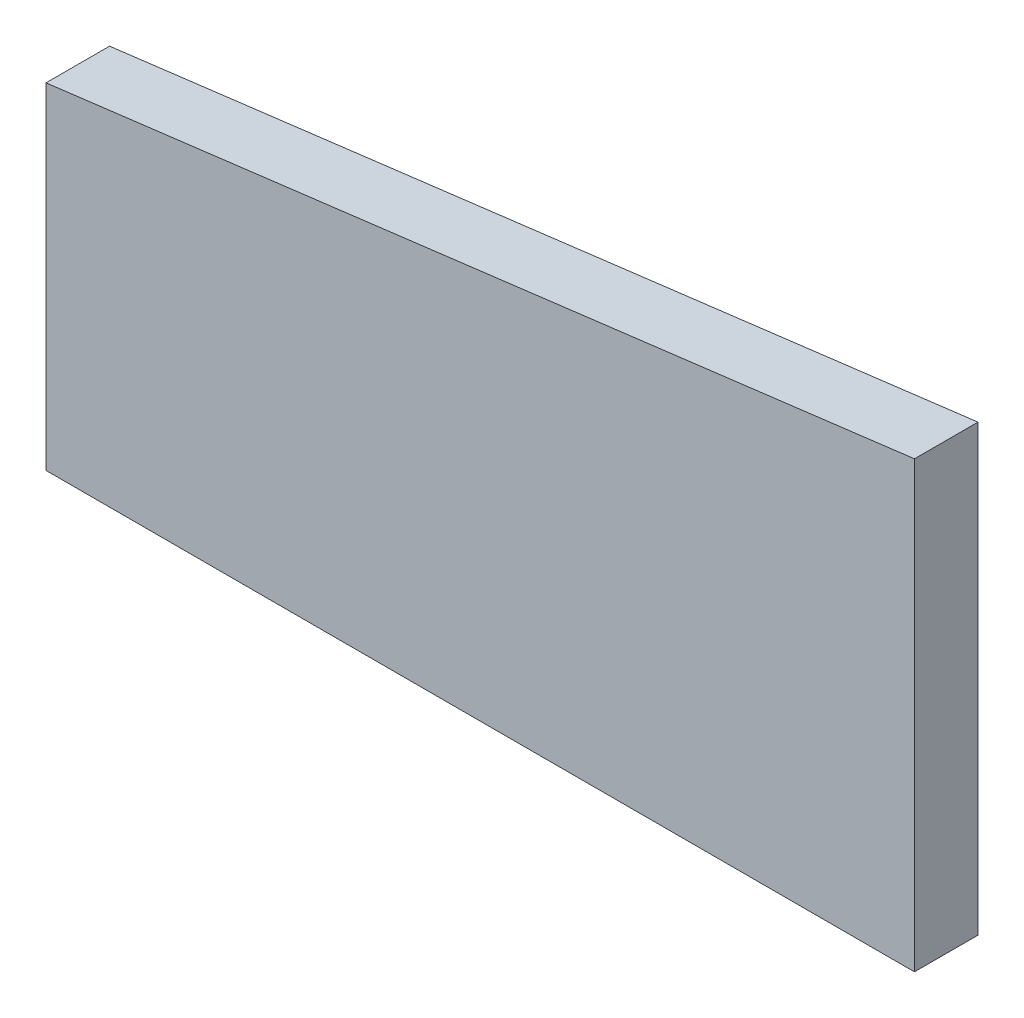
SolidWorks part; units mm, degrees
material "Pine"
ref_plane "Front Plane" through (0, 0, 0) normal (0, 0, 1) x (1, 0, 0)
ref_plane "Top Plane" through (0, 0, 0) normal (0, 1, 0) x (1, 0, 0)
ref_plane "Right Plane" through (0, 0, 0) normal (1, 0, 0) x (0, 0, -1)
sketch "Sketch2" plane through (0, 0, 0) normal (0, 0, 1) x (1, 0, 0)
  line L0 (232.7863, 27.1947) -> (486.7863, 27.1947)
  line L1 (486.7863, 27.1947) -> (486.7863, 179.5947)
  line L2 (486.7863, 179.5947) -> (79.2003, 128.6129)
  line L3 (232.7863, 128.6253) -> (232.7863, 27.1947)
  line L4 (486.7863, 160.3962) -> (81.5647, 109.7102)
  line L5 (251.8363, 131.0081) -> (251.8363, 27.1947)
  line L6 (467.7363, 158.0134) -> (251.8363, 131.0081) construction
  line L7 (467.7363, 27.1947) -> (467.7363, 158.0134)
  line L8 (251.8363, 46.2447) -> (467.7363, 46.2447) construction
  line L9 (251.8363, 131.0081) -> (251.8363, 46.2447) construction
  line L10 (467.7363, 46.2447) -> (467.7363, 158.0134) construction
  line L11 (486.7863, 160.3962) -> (484.4219, 179.2989)
  line L12 (486.7863, 27.1947) -> (486.7863, 179.5947) construction
  line L13 (486.7863, 179.5947) -> (232.7863, 147.8238) construction
  line L14 (81.5647, 109.7102) -> (60.2851, 279.8345) construction
  line L15 (232.7863, 147.8238) -> (232.7863, 27.1947) construction
  line L16 (81.5647, 109.7102) -> (79.2003, 128.6129)
  line L17 (484.4219, 179.2989) -> (230.4219, 147.528) construction
  line L22 (616.7284, 349.4357) -> (60.2851, 279.8345) construction
  line L23 (638.0079, 179.3114) -> (616.7284, 349.4357) construction
  line L24 (232.7863, 128.6253) -> (230.4219, 147.528) construction
  line L25 (232.7863, 27.1947) -> (486.7863, 27.1947) construction
  dimension "D1" = 97.13
sketch "Sketch5" plane through (0, 0, 0) normal (0, 0, 1) x (1, 0, 0)
  line L0 (226.4363, 27.1947) -> (486.7863, 27.1947)
  line L1 (486.7863, 27.1947) -> (486.7863, 179.5947)
  line L2 (486.7863, 179.5947) -> (79.2003, 128.6129)
  line L3 (226.4363, 131.0081) -> (226.4363, 27.1947)
  line L4 (486.7863, 160.3962) -> (81.5647, 109.7102)
  line L6 (467.7363, 158.0134) -> (251.8363, 131.0081) construction
  line L8 (251.8363, 46.2447) -> (467.7363, 46.2447) construction
  line L9 (251.8363, 131.0081) -> (251.8363, 46.2447) construction
  line L10 (467.7363, 46.2447) -> (467.7363, 158.0134) construction
  line L11 (486.7863, 160.3962) -> (484.4219, 179.2989)
  line L12 (486.7863, 27.1947) -> (486.7863, 179.5947) construction
  line L13 (486.7863, 179.5947) -> (232.7863, 147.8238) construction
  line L14 (81.5647, 109.7102) -> (60.2851, 279.8345) construction
  line L15 (232.7863, 147.8238) -> (232.7863, 27.1947) construction
  line L16 (81.5647, 109.7102) -> (79.2003, 128.6129)
  line L17 (484.4219, 179.2989) -> (230.4219, 147.528) construction
  line L22 (616.7284, 349.4357) -> (60.2851, 279.8345) construction
  line L23 (638.0079, 179.3114) -> (616.7284, 349.4357) construction
  line L24 (232.7863, 128.6253) -> (230.4219, 147.528) construction
  line L25 (232.7863, 27.1947) -> (486.7863, 27.1947) construction
  dimension "D1" = 97.13
extrude "Boss-Extrude3" add sketch "Sketch5" along normal blind 19.05
